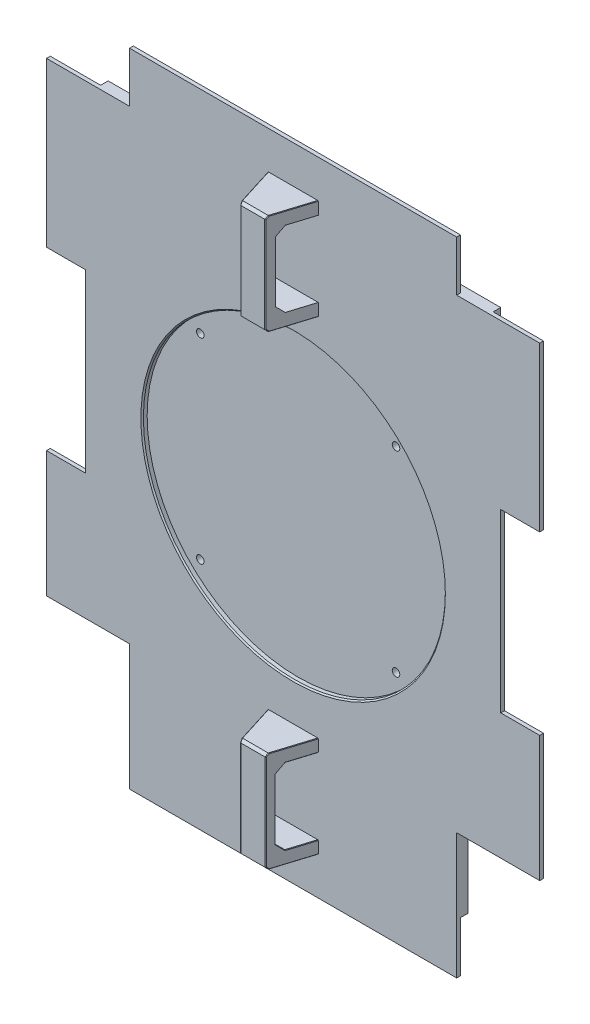
SolidWorks part; units mm, degrees
ref_plane "前视基准面" through (0, 0, 0) normal (0, 0, 1) x (1, 0, 0)
ref_plane "上视基准面" through (0, 0, 0) normal (0, 1, 0) x (1, 0, 0)
ref_plane "右视基准面" through (0, 0, 0) normal (1, 0, 0) x (0, 0, -1)
other "Configuration Table"
sketch "草图1" plane through (0, 0, 0) normal (0, 0, 1) x (1, 0, 0)
  line L1 (-78, 92.5) -> (78, 92.5)
  line L2 (-78, 92.5) -> (-78, -92.5)
  line L3 (-78, -92.5) -> (78, -92.5)
  line L4 (78, 92.5) -> (78, -92.5)
  dimension "D1" = 185
  dimension "D2" = 156
  dimension "D3" = 78
  dimension "D4" = 92.5
extrude "凸台-拉伸1" add sketch "草图1" along normal blind 3
sketch "草图2" plane through (0, 0, 3) normal (0, 0, 1) x (1, 0, 0)
  line L0 (-78, -92.5) -> (78, -92.5) construction
  line L1 (-65, -92.5) -> (65, -92.5)
  line L2 (-65, -92.5) -> (-65, -122.5)
  line L3 (-65, -122.5) -> (65, -122.5)
  line L4 (65, -92.5) -> (65, -122.5)
  dimension "D1" = 30
  dimension "D2" = 130
  dimension "D3" = 65
extrude "凸台-拉伸2" add sketch "草图2" against normal blind 3
sketch "草图3" plane through (0, 0, 3) normal (0, 0, 1) x (1, 0, 0)
  line L0 (78, -92.5) -> (78, 92.5) construction
  line L1 (-82.5, 92.5) -> (-65, 92.5)
  line L2 (-82.5, 92.5) -> (-82.5, -92.5)
  line L3 (-82.5, -92.5) -> (-65, -92.5)
  line L4 (82.5, 92.5) -> (82.5, -92.5)
  line L5 (-78, 92.5) -> (-78, -92.5) construction
  line L6 (78, 92.5) -> (-78, 92.5) construction
  line L7 (65, 92.5) -> (82.5, 92.5)
  line L9 (-65, 92.5) -> (-65, 112.5)
  line L10 (-65, 112.5) -> (65, 112.5)
  line L11 (65, 92.5) -> (65, 112.5)
  line L12 (65, -92.5) -> (78, -92.5) construction
  line L13 (-65, -122.5) -> (65, -122.5) construction
  line L15 (-65, -92.5) -> (-65, -142.5)
  line L16 (-65, -142.5) -> (65, -142.5)
  line L17 (65, -92.5) -> (65, -142.5)
  line L18 (65, -122.5) -> (65, -92.5) construction
  line L19 (65, -92.5) -> (82.5, -92.5)
  dimension "D1" = 4.5
  dimension "D2" = 4.5
  dimension "D3" = 20
  dimension "D4" = 130
  dimension "D5" = 13
  dimension "D6" = 20
extrude "凸台-拉伸3" add sketch "草图3" along normal blind 2
sketch "草图4" plane through (0, 0, 5) normal (0, 0, 1) x (1, 0, 0)
  line L0 (0, 0) -> (0, 50000) construction
  line L1 (-82.5, -92.5) -> (-98, -92.5)
  line L2 (-82.5, -92.5) -> (-82.5, -42.5)
  line L3 (-82.5, -42.5) -> (-98, -42.5)
  line L4 (-98, -92.5) -> (-98, -42.5)
  line L5 (-82.5, 92.5) -> (-98, 92.5)
  line L6 (-82.5, 92.5) -> (-82.5, 27.5)
  line L7 (-82.5, 27.5) -> (-98, 27.5)
  line L8 (-98, 92.5) -> (-98, 27.5)
  line L9 (98, 92.5) -> (98, 27.5)
  line L10 (82.5, 27.5) -> (98, 27.5)
  line L11 (82.5, 92.5) -> (82.5, 27.5)
  line L12 (82.5, 92.5) -> (98, 92.5)
  line L13 (98, -92.5) -> (98, -42.5)
  line L14 (82.5, -42.5) -> (98, -42.5)
  line L15 (82.5, -92.5) -> (82.5, -42.5)
  line L16 (82.5, -92.5) -> (98, -92.5)
  dimension "D1" = 15.5
  dimension "D2" = 50
  dimension "D3" = 15.5
  dimension "D4" = 65
extrude "凸台-拉伸4" add sketch "草图4" against normal blind 2
sketch "草图5" plane through (0, 0, 5) normal (0, 0, 1) x (1, 0, 0)
  line L1 (65, 112.5) -> (-65, 112.5) construction
  line L2 (0, -12.5) -> (0, -50012.5) construction
  line L3 (0, -12.5) -> (-35355.3391, 35342.8391) construction
  circle A1 centre (0, -12.5) radius 55 construction
  circle A6 centre (-38.8909, 26.3909) radius 1.5
  circle A7 centre (38.8909, 26.3909) radius 1.5
  circle A8 centre (38.8909, -51.3909) radius 1.5
  circle A9 centre (-38.8909, -51.3909) radius 1.5
  dimension "D1" = 125
  dimension "D2" = 110
  dimension "D3" = 45
  dimension "D4" = 3
  dimension "D5" = 4
extrude "切除-拉伸1" cut sketch "草图5" against normal through all
chamfer "倒角1" distance 0.5 angle 45 8 edges at (-78, 0, 0) (-71.5, -92.5, 0) (-65, -107.5, 0) (0, -122.5, 0) (65, -107.5, 0) (71.5, -92.5, 0) (78, 0, 0) (0, 92.5, 0)
chamfer "倒角2" distance 0.5 angle 45 16 edges at (-88, -92.5, 3) (0, -142.5, 3) (65, -132.5, 3) (88, -92.5, 3) (65, 102.5, 3) (0, 112.5, 3) (82.5, -7.5, 3) (-82.5, -7.5, 3) (90.25, -42.5, 3) (98, -67.5, 3) (98, 60, 3) (90.25, 27.5, 3) (-90.25, 27.5, 3) (-98, 60, 3) (-98, -67.5, 3) (-90.25, -42.5, 3)
chamfer "倒角3" distance 0.5 angle 45 1 edges at (-65, -132.25, 3)
sketch "草图6" plane through (0, 0, 5) normal (0, 0, 1) x (1, 0, 0)
  line L0 (65, 112.5) -> (-65, 112.5) construction
  circle A0 centre (0, -12.5) radius 60
  dimension "D1" = 125
  dimension "D2" = 120
extrude "切除-拉伸2" cut sketch "草图6" against normal blind 2
chamfer "倒角4" distance 0.5 angle 45 1 edges at (60, -12.5, 5)
sketch "草图7" plane through (0, 0, 0) normal (1, 0, 0) x (0, 0, -1)
  line L0 (-5, 97.5) -> (-21, 97.5)
  line L1 (-5, 27.5) -> (-5, 92.5) construction
  line L2 (-21, 97.5) -> (-21, 57.5)
  line L3 (-21, 57.5) -> (-5, 57.5)
  line L4 (-5, 57.5) -> (-5, 62.5)
  line L5 (-5, 62.5) -> (-18, 62.5)
  line L6 (-18, 62.5) -> (-18, 92.5)
  line L7 (-18, 92.5) -> (-5, 92.5)
  line L8 (-5, 92.5) -> (-5, 97.5)
  line L9 (-5, 112.5) -> (-3.5, 112.5) construction
  dimension "D1" = 5
  dimension "D2" = 5
  dimension "D3" = 30
  dimension "D4" = 3
  dimension "D5" = 16
  dimension "D6" = 15
extrude "凸台-拉伸5" add sketch "草图7" along normal blind 10 and the other way blind 10
sketch "草图8" plane through (0, 97.5, 0) normal (0, 1, 0) x (1, 0, 0)
  line L0 (-10, -5) -> (-5, -21)
  line L1 (-10, -21) -> (10, -21) construction
  line L2 (-5, -21) -> (-10, -21)
  line L3 (-10, -5) -> (-10, -21)
  line L4 (0, -5) -> (0, -50005) construction
  line L5 (65, -5) -> (-65, -5) construction
  line L6 (10, -5) -> (10, -21)
  line L7 (5, -21) -> (10, -21)
  line L8 (10, -5) -> (5, -21)
  point P11 (0, -5)
  dimension "D1" = 5
extrude "切除-拉伸3" cut sketch "草图8" against normal through all
ref_plane "基准面1" through (0, -15, 0) normal (0, -1, 0) x (-1, 0, 0)
mirror "镜向2" about plane through (0, -15, 0) normal (0, -1, 0) of "凸台-拉伸5", "切除-拉伸3"
chamfer "倒角5" distance 3 angle 45 4 edges at (0, -122.5, 18) (0, -92.5, 18) (0, 62.5, 18) (0, 92.5, 18)
chamfer "倒角6" distance 1 angle 45 4 edges at (0, -87.5, 21) (0, -127.5, 21) (0, 57.5, 21) (0, 97.5, 21)
chamfer "倒角7" distance 0.2 angle 45 25 edges at (7.6562, 97.5, 12.5) (5.1562, 97, 20.5) (7.6563, 57.5, 12.5) (5.1563, 58, 20.5) (5, 77.5, 21) (-7.6562, 97.5, 12.5) (-5.1562, 97, 20.5) (-7.6563, 57.5, 12.5) (-5.1563, 58, 20.5) (-5, 77.5, 21) (-7.6562, -87.5, 12.5) (-5.1562, -88, 20.5) (-5, -107.5, 21) (-7.6562, -127.5, 12.5) (-5.1562, -127, 20.5) (5.1562, -88, 20.5) (7.6562, -87.5, 12.5) (8.4375, -92.5, 10) (6.4062, -94, 16.5) (8.4375, -122.5, 10) (6.4063, -121, 16.5) (5.1562, -127, 20.5) (7.6562, -127.5, 12.5) (5.9375, -107.5, 18) (5, -107.5, 21)
